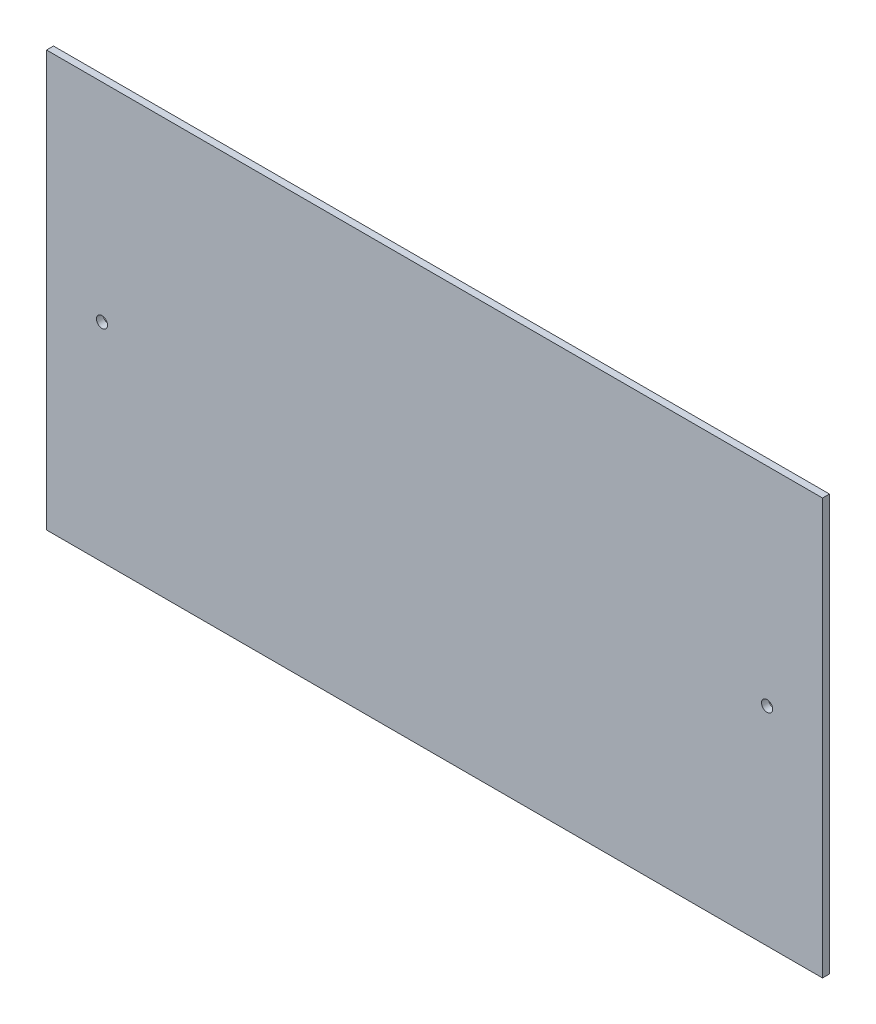
SolidWorks part; units mm, degrees
material "Acrilico (impatto medio-alto)"
ref_plane "Piano frontale" through (0, 0, 0) normal (0, 0, 1) x (1, 0, 0)
ref_plane "Piano superiore" through (0, 0, 0) normal (0, 1, 0) x (1, 0, 0)
ref_plane "Piano destro" through (0, 0, 0) normal (1, 0, 0) x (0, 0, -1)
sketch "Schizzo1" plane through (0, 0, 0) normal (0, 0, 1) x (1, 0, 0)
  line L1 (0, 0) -> (280, 0)
  line L3 (0, 150) -> (280, 150)
  line L14 (0, 0) -> (0, 150)
  line L15 (280, 0) -> (280, 150)
  dimension "D1" = 150
  dimension "D2" = 280
extrude "Estrusione-Estrusione1" add sketch "Schizzo1" along normal blind 2.5
sketch "Schizzo2" plane through (0, 0, 2.5) normal (0, 0, 1) x (1, 0, 0)
  circle A0 centre (260, 75) radius 2
  circle A1 centre (20, 75) radius 2
  dimension "D1" = 4
extrude "Taglio-Estrusione1" cut sketch "Schizzo2" against normal blind 10
